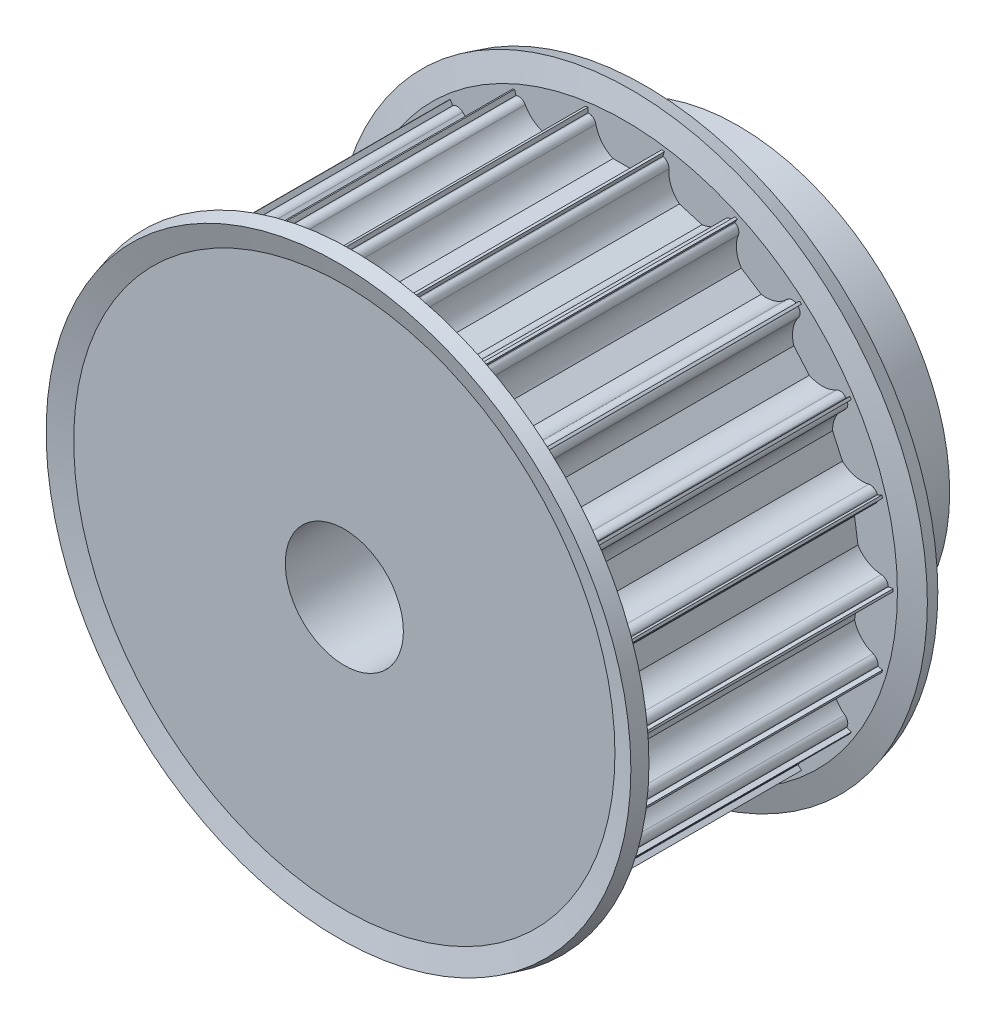
SolidWorks part; units mm, degrees
ref_plane "Front Plane" through (0, 0, 0) normal (0, 0, 1) x (1, 0, 0)
ref_plane "Top Plane" through (0, 0, 0) normal (0, 1, 0) x (1, 0, 0)
ref_plane "Right Plane" through (0, 0, 0) normal (1, 0, 0) x (0, 0, -1)
ref_axis "Axis1" through (0, 0, 111.0698) along (0, 0, -1)
sketch "Sketch1" plane through (0, 0, 0) normal (1, 0, 0) x (0, 0, -1)
  line L0 (0, 6) -> (0, 27.25)
  line L1 (0, 27.25) -> (30, 27.25)
  line L2 (30, 27.25) -> (30, 21.5)
  line L3 (30, 21.5) -> (40, 21.5)
  line L4 (40, 21.5) -> (40, 6)
  line L5 (40, 6) -> (0, 6)
  dimension "D1" = 6
  dimension "D2" = 21.25
  dimension "D3" = 15.5
  dimension "D4" = 30
  dimension "D5" = 10
revolve "Revolve1" add sketch "Sketch1" angle 360 about axis through (0, 0, 111.0698) along (0, 0, -1)
sketch "Sketch6" plane through (0, 0, 0) normal (0, 0, 1) x (1, 0, 0)
  line L0 (3.6742, 26.5) -> (3.75, 26.5)
  line L1 (-3.75, 28.5) -> (3.75, 28.5)
  line L2 (-3.75, 28.5) -> (-3.75, 26.5)
  line L3 (-3.75, 26.5) -> (-3.6742, 26.5)
  line L4 (3.75, 28.5) -> (3.75, 26.5)
  line L5 (-1.199, 23.75) -> (1.199, 23.75)
  arc A0 (-2.9394, 25.9) -> (-1.199, 23.75) centre (0, 26.5) ccw
  arc A1 (-2.9394, 25.9) -> (-3.6742, 26.5) centre (-3.6742, 25.75) ccw
  arc A2 (2.9394, 25.9) -> (3.6742, 26.5) centre (3.6742, 25.75) cw
  arc A3 (1.199, 23.75) -> (2.9394, 25.9) centre (0, 26.5) ccw
  point P7 (0, 0)
  dimension "D1" = 3
  dimension "D5" = 0.75
  dimension "D6" = 0.75
  dimension "D2" = 2
  dimension "D3" = 7.5
  dimension "D4" = 26.5
  dimension "D7" = 2.75
extrude "Cut-Extrude4" cut sketch "Sketch6" against normal blind 35
pattern_circular "CirPattern1" count 22 over 360 about axis through (0, 0, 0) along (0, 0, 1) of "Cut-Extrude4"
sketch "Sketch7" plane through (0, 0, 0) normal (1, 0, 0) x (0, 0, -1)
  line L0 (0, 25.679) -> (0, 23.1257) construction
  line L1 (0, 22.6907) -> (1.5, 22.6907)
  line L2 (0, 22.6907) -> (0, 27.6907)
  line L3 (0, 27.6907) -> (1.5, 27.6907) construction
  line L4 (1.5, 22.6907) -> (1.5, 27.6907)
  line L5 (1.5, 27.6907) -> (0.0511, 27.3025) construction
  line L6 (1.5, 27.6907) -> (0.8569, 30.0907)
  line L7 (0.0511, 27.3025) -> (-0.592, 29.7025)
  line L8 (0.8569, 30.0907) -> (-0.592, 29.7025)
  line L9 (30, 26.9907) -> (0, 26.9907) construction
  line L10 (15, 26.9539) -> (15, -34.6073) construction
  line L11 (0, 26.9539) -> (30, 26.9539) construction
  line L12 (28.5, 27.6907) -> (29.9489, 27.3025) construction
  line L13 (30, 27.6907) -> (28.5, 27.6907) construction
  line L14 (29.1431, 30.0907) -> (30.592, 29.7025)
  line L15 (29.9489, 27.3025) -> (30.592, 29.7025)
  line L16 (28.5, 27.6907) -> (29.1431, 30.0907)
  line L17 (28.5, 22.6907) -> (28.5, 27.6907)
  line L18 (30, 22.6907) -> (30, 27.6907)
  line L19 (30, 22.6907) -> (28.5, 22.6907)
  dimension "D1" = 1.5
  dimension "D2" = 5
  dimension "D3" = 1.5
  dimension "D4" = 165
  dimension "D5" = 2.4
  dimension "D6" = 0.7
revolve "Revolve2" add sketch "Sketch7" angle 360 about axis through (0, 0, 111.0698) along (0, 0, -1)
